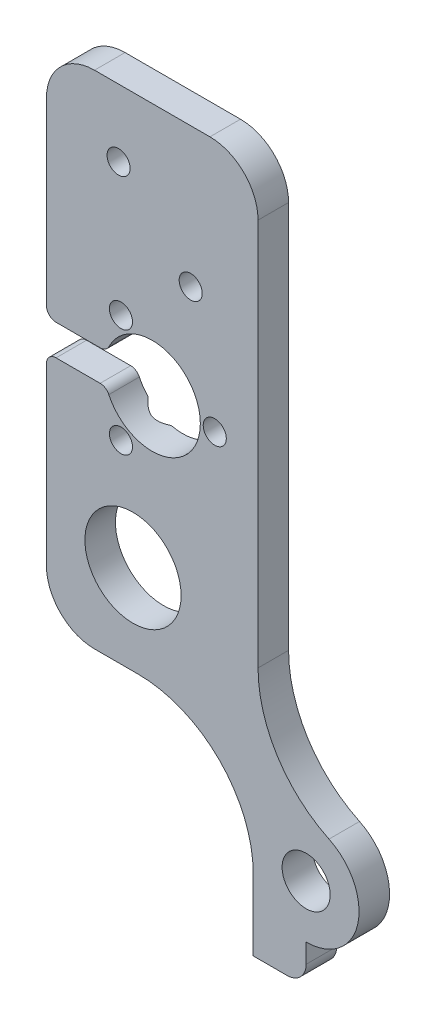
SolidWorks part; units mm, degrees
material "6061-T4 (SS)"
ref_plane "Front" through (0, 0, 0) normal (0, 0, 1) x (1, 0, 0)
ref_plane "Top" through (0, 0, 0) normal (0, 1, 0) x (1, 0, 0)
ref_plane "Right" through (0, 0, 0) normal (1, 0, 0) x (0, 0, -1)
sketch "Sketch1" plane through (0, 0, 0) normal (0, 0, 1) x (1, 0, 0)
  line L7 (-16, 35.6791) -> (-19.25, 41.3082) construction
  line L8 (0, -5.5) -> (-7, -5.5)
  line L9 (-7, -5.5) -> (-7, -9)
  line L57 (-7, -9) -> (-12, -9)
  line L58 (-12, -9) -> (-12, -2.5)
  line L60 (-27, 4.4946) -> (-27, 62)
  line L61 (-27, 62) -> (-5, 62)
  line L62 (-5, 62) -> (-5, 32.1963)
  line L63 (-5, 32.1963) -> (-9, 28.1963)
  line L64 (-9, 28.1963) -> (-9, 10.2653)
  line L65 (-9, 10.2653) -> (2.3244, 4.9847)
  line L66 (-12, -2.5) -> (-27, 4.4946)
  line L67 (-16, 35.6791) -> (-5, 35.6791) construction
  line L68 (-16, 35.6791) -> (-19.25, 30.0499) construction
  circle A8 centre (0, 0) radius 2.5
  arc A9 (0, -5.5) -> (2.3244, 4.9847) centre (0, 0) ccw
  circle A10 centre (0, 0) radius 5.5 construction
  circle A11 centre (-18, 19.2) radius 5
  circle A12 centre (-18, 19.2) radius 9 construction
  circle A13 centre (-16, 35.6791) radius 5
  circle A14 centre (-16, 35.6791) radius 6.5 construction
  circle A16 centre (-9.5, 35.6791) radius 1
  circle A18 centre (-19.25, 30.0499) radius 1
  circle A19 centre (-19.25, 41.3082) radius 1
  point P47 (-16, 62)
  dimension "D4" = 120
  dimension "D5" = 120
  dimension "D6" = 2
  dimension "D7" = 2.5
  dimension "D22" = 5
  dimension "D27" = 10
  dimension "D33" = 10
  dimension "D37" = 13
  dimension "D1" = 28.1963
  dimension "D24" = 9
  dimension "D25" = 5
  dimension "D26" = 7
  dimension "D28" = 18
  dimension "D30" = 115
  dimension "D31" = 135
  dimension "D32" = 19.2
  dimension "D34" = 16.6
  dimension "D35" = 16
  dimension "D36" = 62
  dimension "D23" = 3
  dimension "D29" = 4
extrude "Boss-Extrude1" add sketch "Sketch1" along normal blind 3.175
sketch "L-Bar_Outline" plane through (0, 0, 0) normal (0, 0, -1) x (-1, 0, 0)
  line L0 (10, 57) -> (22, 57) construction
  line L1 (22, 57) -> (22, 53) construction
  line L2 (22, 53) -> (14, 53) construction
  line L3 (14, 53) -> (14, 45) construction
  line L4 (14, 45) -> (10, 45) construction
  line L5 (10, 45) -> (10, 57) construction
  line L6 (27, 4.4946) -> (27, 62) construction
  line L7 (27, 62) -> (5, 62) construction
  line L8 (12, 45) -> (12, 55) construction
  line L9 (12, 55) -> (22, 55) construction
  line L10 (10, 47.5) -> (14, 47.5) construction
  line L11 (19.5, 57) -> (19.5, 53) construction
  dimension "D1" = 12
  dimension "D2" = 4
  dimension "D3" = 4
  dimension "D4" = 12
  dimension "D5" = 5
  dimension "D6" = 5
  dimension "D7" = 2.5
  dimension "D8" = 2.5
hole_wizard "CSK for M2 Flat Head Machine Screw1" positions "Sketch3" profile "Sketch5" countersink size "M2" standard "ANSI Metric" end condition through all
sketch "Sketch3" plane through (0, 0, 0) normal (0, 0, -1) x (-1, 0, 0)
  line L0 (19.5, 57) -> (19.5, 53) construction
  line L1 (10, 47.5) -> (14, 47.5) construction
  point P0 (19.5, 55)
  point P4 (12, 47.5)
sketch "Sketch5" plane through (-19.5, 55, 0) normal (1, 0, 0) x (0, 1, 0)
  line L0 (0, 0) -> (0, 3.175)
  line L1 (0, 3.175) -> (1.2, 3.175)
  line L2 (1.2, 3.175) -> (1.2, 1)
  line L3 (1.2, 1) -> (2.2, 0)
  line L5 (2.2, 0) -> (0, 0)
  line L6 (-1.2, 1) -> (-2.2, 0) construction
  line L11 (0, -6.35) -> (0, 107.95) construction
  dimension "Thru Hole Dia." = 2.4
  dimension "Thru Hole Depth" = 3.175
  dimension "Near C'Sink Dia." = 4.4
  dimension "Near C'Sink Angle" = 90
sketch "Sketch6" plane through (0, 0, 0) normal (0, 0, -1) x (-1, 0, 0)
  line L0 (27, 37.3) -> (27, 34.1)
  line L1 (27, 4.4946) -> (27, 62) construction
  line L3 (27, 37.3) -> (19, 37.3)
  line L4 (19, 37.3) -> (19, 34.1)
  line L5 (19, 34.1) -> (27, 34.1)
  point P0 (19, 35.7)
  dimension "D1" = 3.2
  dimension "D2" = 8
  dimension "D3" = 35.7
extrude "MotorShaftCutOut" cut sketch "Sketch6" against normal through all
fillet "5mm_Fillet" radius 5 7 edges at (-9, 10.2653, 1.5875) (-9, 28.1963, 1.5875) (-5, 32.1963, 1.5875) (-12, -2.5, 1.5875) (-27, 4.4946, 1.5875) (-27, 62, 1.5875) (-5, 62, 1.5875)
fillet "1mm_Fillet" radius 1 6 edges at (-7, -9, 1.5875) (-7, -5.5, 1.5875) (-20.7441, 34.1, 1.5875) (-20.73, 37.3, 1.5875) (-27, 34.1, 1.5875) (-27, 37.3, 1.5875)
sketch "Sketch7" plane through (0, 0, 0) normal (0, 0, -1) x (-1, 0, 0)
  line L0 (12.0472, -5) -> (17.2772, 6.9015)
  line L1 (21.8547, 9.89) -> (27, 9.89)
  line L2 (27, 7.68) -> (27, 33.1) construction
  line L3 (27, 9.89) -> (27, -5)
  line L4 (27, -5) -> (12.0472, -5)
  line L5 (8, -9) -> (12, -9) construction
  arc A0 (14.8869, -1.1538) -> (12, -5.6854) centre (17, -5.6854) ccw construction
  arc A1 (17.2772, 6.9015) -> (21.8547, 9.89) centre (21.8547, 4.89) cw
  dimension "D1" = 5
  dimension "D2" = 4
  dimension "D3" = 14.89
  dimension "D4" = 13
extrude "Cut-Extrude1" cut sketch "Sketch7" against normal through all
fillet "Fillet1" radius 5 1 edges at (-27, 9.89, 1.5875)
sketch "Sketch8" plane through (0, 0, 0) normal (0, 0, -1) x (-1, 0, 0)
  line L0 (0, -5.5) -> (0, -9.5)
  line L1 (0, -9.5) -> (5.5, -9.5)
  line L2 (5.5, -9.5) -> (5.5, 0)
  line L18 (21.8547, 9.89) -> (22, 9.89)
  line L19 (27, 14.89) -> (27, 33.1)
  line L20 (26, 34.1) -> (21.4174, 34.1)
  line L21 (21.3973, 37.3) -> (26, 37.3)
  line L22 (27, 38.3) -> (27, 57)
  line L23 (22, 62) -> (10, 62)
  line L24 (5, 57) -> (5, 34.2674)
  line L25 (6.4645, 30.7319) -> (7.5355, 29.6608)
  line L26 (9, 26.1253) -> (9, 13.4507)
  line L27 (6.1131, 8.9192) -> (-2.3244, 4.9847)
  line L28 (0, -5.5) -> (6, -5.5)
  line L29 (7, -6.5) -> (7, -8)
  line L30 (8, -9) -> (12, -9)
  line L31 (12, -9) -> (12, -5.6854)
  line L32 (13.1456, -2.5005) -> (17.2772, 6.9015)
  line L33 (21.8547, 9.89) -> (22, 9.89)
  line L34 (27, 14.89) -> (27, 33.1)
  line L35 (26, 34.1) -> (21.4174, 34.1)
  line L36 (21.3973, 37.3) -> (26, 37.3)
  line L37 (27, 38.3) -> (27, 57)
  line L38 (22, 62) -> (10, 62)
  line L39 (5, 57) -> (5, 34.2674)
  line L40 (6.4645, 30.7319) -> (7.5355, 29.6608)
  line L41 (9, 26.1253) -> (9, 13.4507)
  line L42 (6.1131, 8.9192) -> (-2.3244, 4.9847)
  line L43 (0, -5.5) -> (6, -5.5)
  line L44 (7, -6.5) -> (7, -8)
  line L45 (8, -9) -> (12, -9)
  line L46 (12, -9) -> (12, -5.6854)
  line L47 (13.1456, -2.5005) -> (17.2772, 6.9015)
  circle A0 centre (0, 0) radius 5.5
  arc A17 (22, 9.89) -> (27, 14.89) centre (22, 14.89) ccw
  arc A18 (27, 33.1) -> (26, 34.1) centre (26, 33.1) ccw
  arc A19 (21.4174, 34.1) -> (20.5145, 33.5298) centre (21.4174, 33.1) ccw
  arc A20 (20.4977, 37.8632) -> (20.5145, 33.5298) centre (16, 35.6791) ccw
  arc A21 (20.4977, 37.8632) -> (21.3973, 37.3) centre (21.3973, 38.3) ccw
  arc A22 (26, 37.3) -> (27, 38.3) centre (26, 38.3) ccw
  arc A23 (27, 57) -> (22, 62) centre (22, 57) ccw
  arc A24 (10, 62) -> (5, 57) centre (10, 57) ccw
  arc A25 (5, 34.2674) -> (6.4645, 30.7319) centre (10, 34.2674) ccw
  arc A26 (9, 26.1253) -> (7.5355, 29.6608) centre (4, 26.1253) ccw
  arc A27 (6.1131, 8.9192) -> (9, 13.4507) centre (4, 13.4507) ccw
  arc A28 (-2.3244, 4.9847) -> (0, -5.5) centre (0, 0) ccw
  arc A29 (7, -6.5) -> (6, -5.5) centre (6, -6.5) ccw
  arc A30 (7, -8) -> (8, -9) centre (8, -8) ccw
  arc A31 (13.1456, -2.5005) -> (12, -5.6854) centre (17, -5.6854) ccw
  arc A32 (21.8547, 9.89) -> (17.2772, 6.9015) centre (21.8547, 4.89) ccw
  arc A33 (22, 9.89) -> (27, 14.89) centre (22, 14.89) ccw
  arc A34 (27, 33.1) -> (26, 34.1) centre (26, 33.1) ccw
  arc A35 (21.4174, 34.1) -> (20.5145, 33.5298) centre (21.4174, 33.1) ccw
  arc A36 (20.4977, 37.8632) -> (20.5145, 33.5298) centre (16, 35.6791) ccw
  arc A37 (20.4977, 37.8632) -> (21.3973, 37.3) centre (21.3973, 38.3) ccw
  arc A38 (26, 37.3) -> (27, 38.3) centre (26, 38.3) ccw
  arc A39 (27, 57) -> (22, 62) centre (22, 57) ccw
  arc A40 (10, 62) -> (5, 57) centre (10, 57) ccw
  arc A41 (5, 34.2674) -> (6.4645, 30.7319) centre (10, 34.2674) ccw
  arc A42 (9, 26.1253) -> (7.5355, 29.6608) centre (4, 26.1253) ccw
  arc A43 (6.1131, 8.9192) -> (9, 13.4507) centre (4, 13.4507) ccw
  arc A44 (-2.3244, 4.9847) -> (0, -5.5) centre (0, 0) ccw
  arc A45 (7, -6.5) -> (6, -5.5) centre (6, -6.5) ccw
  arc A46 (7, -8) -> (8, -9) centre (8, -8) ccw
  arc A47 (13.1456, -2.5005) -> (12, -5.6854) centre (17, -5.6854) ccw
  arc A48 (21.8547, 9.89) -> (17.2772, 6.9015) centre (21.8547, 4.89) ccw
  line M61 (0, -5.5) -> (6, -5.5)
  dimension "D2" = 4
  dimension "D1" = 0
extrude "Boss-Extrude2" add sketch "Sketch8" against normal up to surface (3.175 mm away) contours L1 L2 L0 M61 up to face at (-14.0453, 21.3563, 3.175)
sketch "Sketch9" plane through (0, 0, 3.175) normal (0, 0, 1) x (1, 0, 0)
  line L0 (-5, 34.2674) -> (-5, 8.4001)
  line L18 (-27, 33.1) -> (-27, 14.89)
  line L19 (-22, 9.89) -> (-21.8547, 9.89)
  line L20 (-17.2772, 6.9015) -> (-13.1456, -2.5005)
  line L21 (-12, -5.6854) -> (-12, -9)
  line L22 (-12, -9) -> (-8, -9)
  line L23 (-7, -8) -> (-7, -6.5)
  line L25 (-5.5, -5.5) -> (-5.5, -9.5)
  line L26 (-5.5, -9.5) -> (0, -9.5)
  line L27 (0, -9.5) -> (0, -5.5)
  line L28 (2.3244, 4.9847) -> (-6.1131, 8.9192)
  line L29 (-9, 13.4507) -> (-9, 26.1253)
  line L30 (-7.5355, 29.6608) -> (-6.4645, 30.7319)
  line L31 (-5, 34.2674) -> (-5, 57)
  line L32 (-10, 62) -> (-22, 62)
  line L33 (-27, 57) -> (-27, 38.3)
  line L34 (-26, 37.3) -> (-21.3973, 37.3)
  line L35 (-21.4174, 34.1) -> (-26, 34.1)
  line L36 (-27, 33.1) -> (-27, 14.89)
  line L37 (-22, 9.89) -> (-21.8547, 9.89)
  line L38 (-17.2772, 6.9015) -> (-13.1456, -2.5005)
  line L39 (-12, -5.6854) -> (-12, -9)
  line L40 (-12, -9) -> (-8, -9)
  line L41 (-7, -8) -> (-7, -6.5)
  line L43 (-5.5, -5.5) -> (-5.5, -9.5)
  line L44 (-5.5, -9.5) -> (0, -9.5)
  line L45 (0, -9.5) -> (0, -5.5)
  line L46 (-5, 8.4001) -> (-6.1131, 8.9192)
  line L47 (-9, 13.4507) -> (-9, 26.1253)
  line L48 (-7.5355, 29.6608) -> (-6.4645, 30.7319)
  line L49 (-5, 34.2674) -> (-5, 57)
  line L50 (-10, 62) -> (-22, 62)
  line L51 (-27, 57) -> (-27, 38.3)
  line L52 (-26, 37.3) -> (-21.3973, 37.3)
  line L53 (-21.4174, 34.1) -> (-26, 34.1)
  line L54 (-6, -5.5) -> (-5.5, -5.5)
  line L55 (-6, -5.5) -> (-5.5, -5.5)
  arc A16 (-27, 14.89) -> (-22, 9.89) centre (-22, 14.89) ccw
  arc A17 (-17.2772, 6.9015) -> (-21.8547, 9.89) centre (-21.8547, 4.89) ccw
  arc A18 (-12, -5.6854) -> (-13.1456, -2.5005) centre (-17, -5.6854) ccw
  arc A19 (-8, -9) -> (-7, -8) centre (-8, -8) ccw
  arc A20 (-6, -5.5) -> (-7, -6.5) centre (-6, -6.5) ccw
  arc A21 (0, -5.5) -> (2.3244, 4.9847) centre (0, 0) ccw
  arc A22 (-9, 13.4507) -> (-6.1131, 8.9192) centre (-4, 13.4507) ccw
  arc A23 (-7.5355, 29.6608) -> (-9, 26.1253) centre (-4, 26.1253) ccw
  arc A24 (-6.4645, 30.7319) -> (-5, 34.2674) centre (-10, 34.2674) ccw
  arc A25 (-5, 57) -> (-10, 62) centre (-10, 57) ccw
  arc A26 (-22, 62) -> (-27, 57) centre (-22, 57) ccw
  arc A27 (-27, 38.3) -> (-26, 37.3) centre (-26, 38.3) ccw
  arc A28 (-21.3973, 37.3) -> (-20.4977, 37.8632) centre (-21.3973, 38.3) ccw
  arc A29 (-20.5145, 33.5298) -> (-20.4977, 37.8632) centre (-16, 35.6791) ccw
  arc A30 (-20.5145, 33.5298) -> (-21.4174, 34.1) centre (-21.4174, 33.1) ccw
  arc A31 (-26, 34.1) -> (-27, 33.1) centre (-26, 33.1) ccw
  arc A32 (-27, 14.89) -> (-22, 9.89) centre (-22, 14.89) ccw
  arc A33 (-17.2772, 6.9015) -> (-21.8547, 9.89) centre (-21.8547, 4.89) ccw
  arc A34 (-12, -5.6854) -> (-13.1456, -2.5005) centre (-17, -5.6854) ccw
  arc A35 (-8, -9) -> (-7, -8) centre (-8, -8) ccw
  arc A36 (-6, -5.5) -> (-7, -6.5) centre (-6, -6.5) ccw
  arc A37 (0, -5.5) -> (2.3244, 4.9847) centre (0, 0) ccw
  arc A38 (-9, 13.4507) -> (-6.1131, 8.9192) centre (-4, 13.4507) ccw
  arc A39 (-7.5355, 29.6608) -> (-9, 26.1253) centre (-4, 26.1253) ccw
  arc A40 (-6.4645, 30.7319) -> (-5, 34.2674) centre (-10, 34.2674) ccw
  arc A41 (-5, 57) -> (-10, 62) centre (-10, 57) ccw
  arc A42 (-22, 62) -> (-27, 57) centre (-22, 57) ccw
  arc A43 (-27, 38.3) -> (-26, 37.3) centre (-26, 38.3) ccw
  arc A44 (-21.3973, 37.3) -> (-20.4977, 37.8632) centre (-21.3973, 38.3) ccw
  arc A45 (-20.5145, 33.5298) -> (-20.4977, 37.8632) centre (-16, 35.6791) ccw
  arc A46 (-20.5145, 33.5298) -> (-21.4174, 34.1) centre (-21.4174, 33.1) ccw
  arc A47 (-26, 34.1) -> (-27, 33.1) centre (-26, 33.1) ccw
  dimension "D1" = 0
extrude "Boss-Extrude3" add sketch "Sketch9" against normal up to surface (3.175 mm away) contours L0 L46 A38 L47 A39 L48 A40 up to face at (-21.7, 55, 0)
sketch "Sketch10" plane through (0, 0, 3.175) normal (0, 0, 1) x (1, 0, 0)
  line L1 (-22, 9.89) -> (-5.5, 9.89)
  line L2 (-22, 9.89) -> (-22, -5.5)
  line L3 (-22, -5.5) -> (-5.5, -5.5)
  line L4 (-5.5, 9.89) -> (-5.5, -5.5)
  line L16 (2.3244, 4.9847) -> (-5, 8.4001)
  line L17 (-5, 8.4001) -> (-5, 57)
  line L18 (-10, 62) -> (-22, 62)
  line L19 (-27, 57) -> (-27, 38.3)
  line L20 (-26, 37.3) -> (-21.3973, 37.3)
  line L21 (-21.4174, 34.1) -> (-26, 34.1)
  line L22 (-27, 33.1) -> (-27, 14.89)
  line L23 (-22, 9.89) -> (-21.8547, 9.89)
  line L24 (-17.2772, 6.9015) -> (-13.1456, -2.5005)
  line L25 (-12, -5.6854) -> (-12, -9)
  line L26 (-12, -9) -> (-8, -9)
  line L27 (-7, -8) -> (-7, -6.5)
  line L29 (-5.5, -5.5) -> (-5.5, -9.5)
  line L30 (-5.5, -9.5) -> (0, -9.5)
  line L31 (0, -9.5) -> (0, -5.5)
  line L32 (2.3244, 4.9847) -> (-5, 8.4001)
  line L33 (-5, 8.4001) -> (-5, 57)
  line L34 (-10, 62) -> (-22, 62)
  line L35 (-27, 57) -> (-27, 38.3)
  line L36 (-26, 37.3) -> (-21.3973, 37.3)
  line L37 (-21.4174, 34.1) -> (-26, 34.1)
  line L38 (-27, 33.1) -> (-27, 14.89)
  line L45 (-5.5, -5.5) -> (-5.5, -9.5)
  line L46 (-5.5, -9.5) -> (0, -9.5)
  line L47 (0, -9.5) -> (0, -5.5)
  line L51 (-6, -5.5) -> (-5.5, -5.5)
  line L52 (-6, -5.5) -> (-5.5, -5.5)
  arc A15 (-5, 57) -> (-10, 62) centre (-10, 57) ccw
  arc A16 (-22, 62) -> (-27, 57) centre (-22, 57) ccw
  arc A17 (-27, 38.3) -> (-26, 37.3) centre (-26, 38.3) ccw
  arc A18 (-21.3973, 37.3) -> (-20.4977, 37.8632) centre (-21.3973, 38.3) ccw
  arc A19 (-20.5145, 33.5298) -> (-20.4977, 37.8632) centre (-16, 35.6791) ccw
  arc A20 (-20.5145, 33.5298) -> (-21.4174, 34.1) centre (-21.4174, 33.1) ccw
  arc A21 (-26, 34.1) -> (-27, 33.1) centre (-26, 33.1) ccw
  arc A22 (-27, 14.89) -> (-22, 9.89) centre (-22, 14.89) ccw
  arc A23 (-17.2772, 6.9015) -> (-21.8547, 9.89) centre (-21.8547, 4.89) ccw
  arc A24 (-12, -5.6854) -> (-13.1456, -2.5005) centre (-17, -5.6854) ccw
  arc A25 (-8, -9) -> (-7, -8) centre (-8, -8) ccw
  arc A26 (-6, -5.5) -> (-7, -6.5) centre (-6, -6.5) ccw
  arc A27 (0, -5.5) -> (2.3244, 4.9847) centre (0, 0) ccw
  arc A29 (-5, 57) -> (-10, 62) centre (-10, 57) ccw
  arc A30 (-22, 62) -> (-27, 57) centre (-22, 57) ccw
  arc A31 (-27, 38.3) -> (-26, 37.3) centre (-26, 38.3) ccw
  arc A32 (-21.3973, 37.3) -> (-20.4977, 37.8632) centre (-21.3973, 38.3) ccw
  arc A33 (-20.5145, 33.5298) -> (-20.4977, 37.8632) centre (-16, 35.6791) ccw
  arc A34 (-20.5145, 33.5298) -> (-21.4174, 34.1) centre (-21.4174, 33.1) ccw
  arc A35 (-26, 34.1) -> (-27, 33.1) centre (-26, 33.1) ccw
  arc A36 (-27, 14.89) -> (-22, 9.89) centre (-22, 14.89) ccw
  arc A41 (0, -5.5) -> (2.3244, 4.9847) centre (0, 0) ccw
  arc M48 (-21.8547, 9.89) -> (-17.2772, 6.9015) centre (-21.8547, 4.89) cw
  line M49 (-17.2772, 6.9015) -> (-13.1456, -2.5005)
  arc M50 (-13.1456, -2.5005) -> (-12, -5.6854) centre (-17, -5.6854) cw
  line M56 (-6, -5.5) -> (-5.5, -5.5)
  dimension "D1" = 0
extrude "Cut-Extrude3" cut sketch "Sketch10" against normal blind 10 and the other way through all contours L4 L1 L3 M48 M49 M50 M56
fillet "Fillet3" radius 12 1 edges at (-5.5, 9.89, 1.5875)
fillet "Fillet4" radius 2 1 edges at (0, -9.5, 1.5875)
fillet "Fillet6" radius 13 1 edges at (-5, 8.4001, 1.5875)
hole_wizard "CSK for M2 Flat Head Machine Screw3" positions "Sketch13" profile "Sketch14" countersink size "M2" standard "ANSI Metric" end condition through all
sketch "Sketch13" plane through (0, 0, 0) normal (0, 0, -1) x (-1, 0, 0)
  point P0 (19.25, 41.3082)
  point P3 (9.5, 35.6791)
  point P6 (19.25, 30.0499)
sketch "Sketch14" plane through (-19.25, 41.3082, 0) normal (1, 0, 0) x (0, 1, 0)
  line L0 (0, 0) -> (0, 3.175)
  line L1 (0, 3.175) -> (1.2, 3.175)
  line L2 (1.2, 3.175) -> (1.2, 1)
  line L3 (1.2, 1) -> (2.2, 0)
  line L5 (2.2, 0) -> (0, 0)
  line L6 (-1.2, 1) -> (-2.2, 0) construction
  line L11 (0, -6.35) -> (0, 107.95) construction
  dimension "Thru Hole Dia." = 2.4
  dimension "Thru Hole Depth" = 3.175
  dimension "Near C'Sink Dia." = 4.4
  dimension "Near C'Sink Angle" = 90
